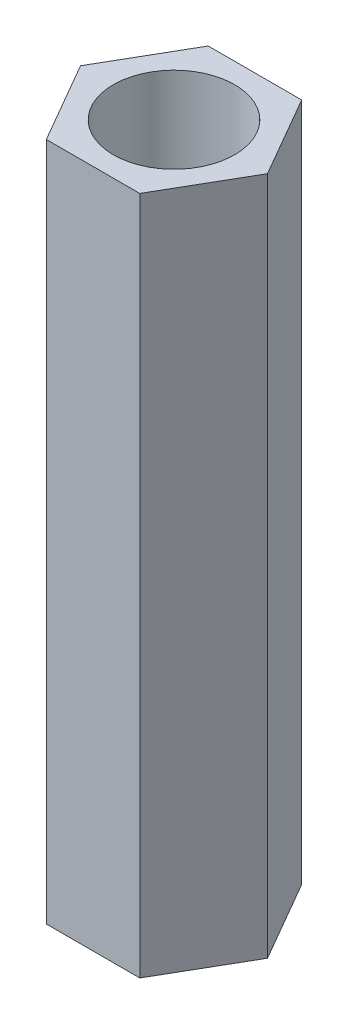
SolidWorks part; units mm, degrees
ref_plane "Front Plane" through (0, 0, 0) normal (0, 0, 1) x (1, 0, 0)
ref_plane "Top Plane" through (0, 0, 0) normal (0, 1, 0) x (1, 0, 0)
ref_plane "Right Plane" through (0, 0, 0) normal (1, 0, 0) x (0, 0, -1)
sketch "Sketch1" plane through (0, 0, 0) normal (0, 1, 0) x (1, 0, 0)
  line L1 (1.7321, -3) -> (3.4641, 0)
  line L2 (3.4641, 0) -> (1.7321, 3)
  line L3 (1.7321, 3) -> (-1.7321, 3)
  line L4 (-1.7321, 3) -> (-3.4641, 0)
  line L5 (-3.4641, 0) -> (-1.7321, -3)
  line L6 (-1.7321, -3) -> (1.7321, -3)
  circle A0 centre (0, 0) radius 3 construction
  circle A1 centre (0, 0) radius 2.25
  dimension "D1" = 4.5
  dimension "D2" = 6
extrude "Boss-Extrude1" add sketch "Sketch1" along normal blind 25.18
